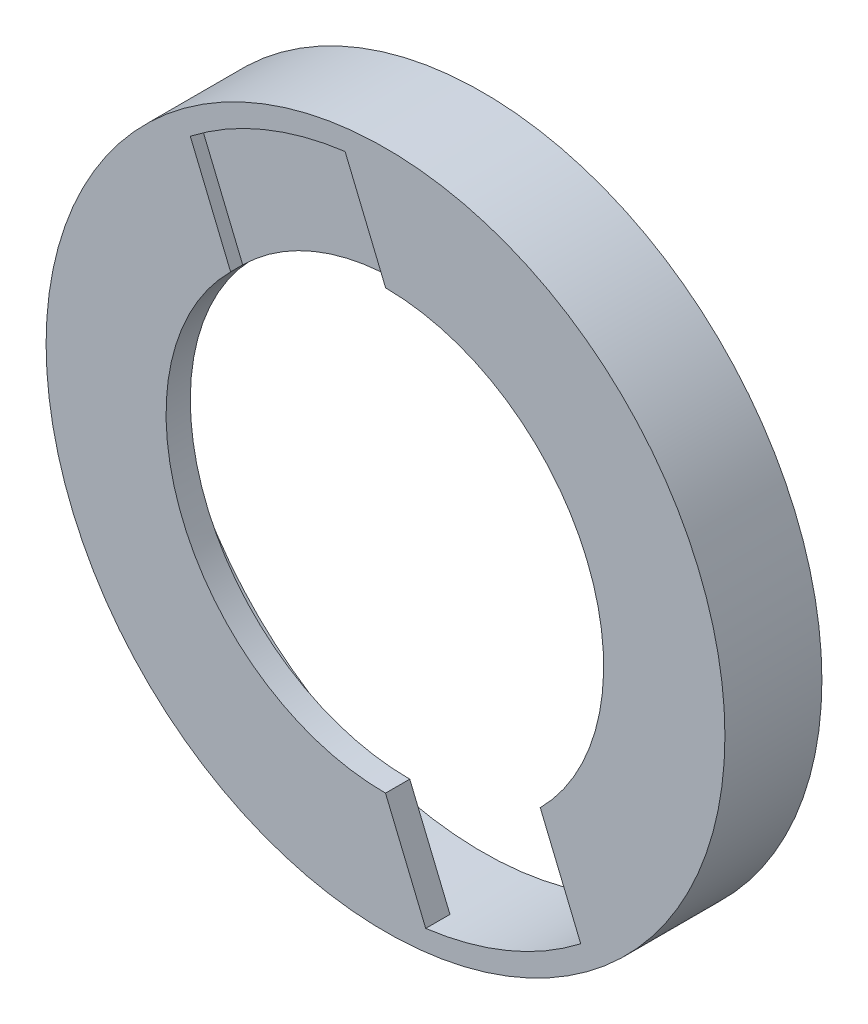
SolidWorks part; units mm, degrees
ref_plane "Front Plane" through (0, 0, 0) normal (0, 0, 1) x (1, 0, 0)
ref_plane "Top Plane" through (0, 0, 0) normal (0, 1, 0) x (1, 0, 0)
ref_plane "Right Plane" through (0, 0, 0) normal (1, 0, 0) x (0, 0, -1)
sketch "Sketch1" plane through (0, 0, 0) normal (0, 0, 1) x (1, 0, 0)
  circle A4 centre (0.0268, 0.0172) radius 14
  circle A6 centre (0.0268, 0.0172) radius 13.15
  dimension "D1" = 26.3
  dimension "D2" = 28
extrude "Boss-Extrude1" add sketch "Sketch1" against normal blind 3
sketch "Sketch2" plane through (0, 0, 0) normal (0, 0, 1) x (1, 0, 0)
  circle A1 centre (0, 0) radius 9.025
  circle A6 centre (0.0268, 0.0172) radius 14 construction
  circle A7 centre (0.0268, 0.0172) radius 14
  dimension "D1" = 18.05
extrude "Boss-Extrude2" add sketch "Sketch2" along normal blind 1
sketch "Sketch3" plane through (0, 0, 0) normal (0, 0, -1) x (-1, 0, 0)
  line L0 (-0.0268, 0.0172) -> (-0.0268, -13.1328)
  line L1 (-0.0268, 0.0172) -> (-9.3253, -9.2812)
  line L2 (-0.0268, 0.1737) -> (-0.0268, 0.0172) construction
  line L3 (-0.0268, 0.0172) -> (-5.0591, -12.1318) construction
  line L4 (-0.0268, -9.025) -> (-1.6849, -13.0278)
  line L5 (-6.4206, -6.3766) -> (-8.0787, -10.3794)
  circle A0 centre (0, 0) radius 9.025 construction
  circle A1 centre (-0.0268, 0.0172) radius 13.15
  circle A2 centre (-0.0268, 0.0172) radius 13.15
  circle A3 centre (0, 0) radius 9.025
  point P11 (0, 0)
  circle M7 centre (0, 0) radius 9.025
  circle M8 centre (-0.0268, 0.0172) radius 13.15
  dimension "D2" = 22.5
  dimension "D1" = 0
extrude "Cut-Extrude1" cut sketch "Sketch3" against normal through all contours L1 L5 L4 M8 M7
sketch "Sketch4" plane through (0, 0, 1) normal (0, 0, 1) x (1, 0, 0)
  line L0 (6.4036, -6.3596) -> (-1.977, 13.8731)
  line L1 (0.0268, -9.025) -> (-8.3614, 11.226)
  line L2 (0.0268, -9.025) -> (1.6849, -13.0278) construction
  circle A0 centre (0.0268, 0.0172) radius 14 construction
  arc A1 (6.4036, -6.3596) -> (0.0268, -9.025) centre (0, 0) ccw construction
  circle A2 centre (0.0268, 0.0172) radius 14
  arc A3 (6.4036, -6.3596) -> (0.0268, -9.025) centre (0, 0) ccw
  circle A4 centre (0.0268, 0.0172) radius 13.15 construction
  circle A5 centre (0.0268, 0.0172) radius 13.15
  arc M8 (0.0268, -9.025) -> (6.4036, -6.3596) centre (0, 0) cw
extrude "Cut-Extrude2" cut sketch "Sketch4" against normal blind 0.5 contours L0 A5 L1 M8
